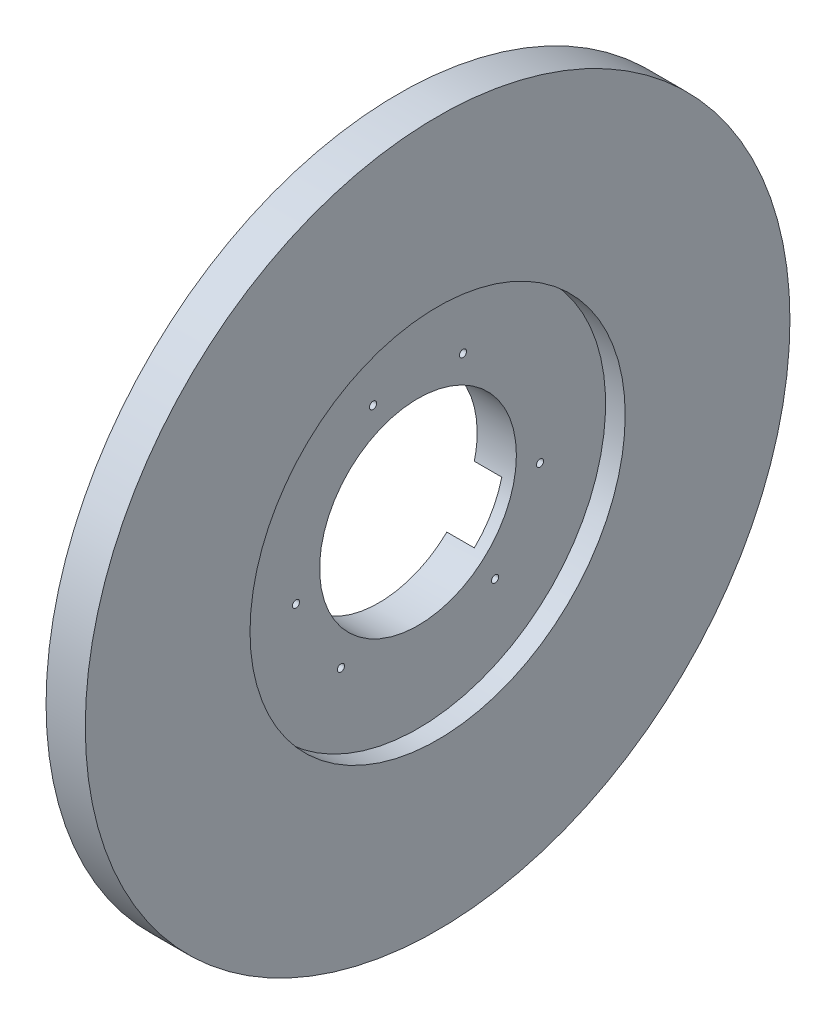
SolidWorks part; units mm, degrees
ref_plane "Front Plane" through (0, 0, 0) normal (0, 0, 1) x (1, 0, 0)
ref_plane "Top Plane" through (0, 0, 0) normal (0, 1, 0) x (1, 0, 0)
ref_plane "Right Plane" through (0, 0, 0) normal (1, 0, 0) x (0, 0, -1)
sketch "Sketch1" plane through (0, 0, 0) normal (1, 0, 0) x (0, 0, -1)
  circle A0 centre (0, 0) radius 89.825
  circle A1 centre (0, 0) radius 47.825
  dimension "D1" = 179.65
  dimension "D2" = 95.65
extrude "Boss-Extrude1" add sketch "Sketch1" along normal blind 10
sketch "Sketch3" plane through (0, 0, 0) normal (-1, 0, 0) x (0, 0, 1)
  circle A0 centre (0, 0) radius 47.825
  dimension "D1" = 95.65
extrude "tbh idk" add sketch "Sketch3" against normal blind 5
sketch "Sketch4" plane through (0, 0, 0) normal (-1, 0, 0) x (0, 0, 1)
  circle A0 centre (0, 0) radius 47.825
  dimension "D1" = 95.65
extrude "Extrusion to Fuel Man" add sketch "Sketch4" along normal blind 5
sketch "Ox Profile" plane through (-5, 0, 0) normal (-1, 0, 0) x (0, 0, 1)
  line L0 (0, 23.8051) -> (0, 34.7601) construction
  line L1 (0, -8.25) -> (0, 8.25) construction
  circle A0 centre (0, 29.2826) radius 0.8262 construction
  circle A1 centre (11.4641, 29.2826) radius 0.9146
  circle A2 centre (-11.4641, 29.2826) radius 0.9146
  point P4 (7.9201, 29.2826)
  point P6 (6.3718, 30.3708)
  point P7 (0, 0)
  point P8 (0, 0)
  point P11 (0, 29.2826)
  point P12 (0, 22.8185)
  point P13 (-2.1016, 23.1697)
  point P14 (0, 0)
  point P15 (6.1202, 27.2022)
  point P16 (0, 34.7601)
  point P19 (-6.4641, 29.2826)
  dimension "D1" = 1.6524
  dimension "D3" = 1.8292
  dimension "D2" = 29.2826
  dimension "D4" = 11.4641
extrude "Ox Downcomer" cut sketch "Ox Profile" against normal up to next
pattern_circular "Ox Orifices" count 3 over 360 about axis through (0, -0.0214, 0) along (1, 0, 0) of "Ox Downcomer"
sketch "Sketch7" plane through (-5, 0, 0) normal (-1, 0, 0) x (0, 0, 1)
  line L0 (-8.7202, 29.2826) -> (8.7202, 29.2826) construction
  line L1 (-31.0915, -4.7131) -> (-11.4641, 29.2826) construction
  line L2 (-33.4678, -3.3412) -> (-13.8404, 30.6545)
  line L3 (31.0915, -4.7131) -> (11.4641, 29.2826) construction
  line L4 (13.8404, 30.6545) -> (33.4678, -3.3412)
  line L5 (-19.6274, -24.5695) -> (19.6274, -24.5695) construction
  line L6 (-19.6274, -27.3134) -> (19.6274, -27.3134)
  circle A0 centre (-11.4641, 29.2826) radius 2.7439 construction
  circle A1 centre (11.4641, 29.2826) radius 2.7439 construction
  arc A2 (-8.7202, 29.2826) -> (8.7202, 29.2826) centre (0, 29.2826) ccw
  circle A3 centre (31.0915, -4.7131) radius 2.7439 construction
  arc A4 (29.7196, -7.0894) -> (20.9994, -22.1932) centre (25.3595, -14.6413) ccw
  circle A5 centre (19.6274, -24.5695) radius 2.7439 construction
  circle A6 centre (-19.6274, -24.5695) radius 2.7439 construction
  arc A7 (-20.9994, -22.1932) -> (-29.7196, -7.0894) centre (-25.3595, -14.6413) ccw
  circle A8 centre (-31.0915, -4.7131) radius 2.7439 construction
  arc A9 (-13.8404, 30.6545) -> (-8.7202, 29.2826) centre (-11.4641, 29.2826) cw
  arc A10 (-33.4678, -3.3412) -> (-29.7196, -7.0894) centre (-31.0915, -4.7131) ccw
  arc A11 (8.7202, 29.2826) -> (13.8404, 30.6545) centre (11.4641, 29.2826) cw
  arc A12 (29.7196, -7.0894) -> (33.4678, -3.3412) centre (31.0915, -4.7131) ccw
  arc A13 (20.9994, -22.1932) -> (19.6274, -27.3134) centre (19.6274, -24.5695) cw
  arc A14 (-20.9994, -22.1932) -> (-19.6274, -27.3134) centre (-19.6274, -24.5695) ccw
  circle A15 centre (0, 0) radius 47.825
  point P25 (0, 0)
  dimension "D2" = 2.7439
  dimension "D3" = 95.65
  dimension "D1" = 3
extrude "Fuel Blockers" cut sketch "Sketch7" against normal blind 5
sketch "Sketch8" plane through (5, 0, 0) normal (1, 0, 0) x (0, 0, -1)
  circle A0 centre (0, 0) radius 25.085
  dimension "D1" = 50.17
extrude "TI Cut Extrude" cut sketch "Sketch8" against normal through all
sketch "Sketch9" plane through (0, 0, 0) normal (-1, 0, 0) x (0, 0, 1)
  line L0 (-13.8404, 30.6545) -> (-33.4678, -3.3412) construction
  line L1 (-13.8404, 30.6545) -> (-33.4678, -3.3412)
  line L3 (33.4678, -3.3412) -> (13.8404, 30.6545)
  line L4 (-19.6274, -27.3134) -> (19.6274, -27.3134)
  line L5 (-13.8404, 30.6545) -> (-33.4678, -3.3412)
  line L6 (33.4678, -3.3412) -> (13.8404, 30.6545)
  line L7 (-19.6274, -27.3134) -> (19.6274, -27.3134)
  line L8 (-13.8404, 30.6545) -> (-33.4678, -3.3412)
  circle A0 centre (0, 0) radius 51.325
  arc A1 (13.8404, 30.6545) -> (8.7202, 29.2826) centre (11.4641, 29.2826) ccw construction
  arc A2 (-33.4678, -3.3412) -> (-29.7196, -7.0894) centre (-31.0915, -4.7131) ccw construction
  arc A3 (13.8404, 30.6545) -> (8.7202, 29.2826) centre (11.4641, 29.2826) ccw
  arc A4 (-33.4678, -3.3412) -> (-29.7196, -7.0894) centre (-31.0915, -4.7131) ccw
  arc A5 (-17.3584, -18.1092) -> (17.3584, -18.1092) centre (0, 0) ccw construction
  arc A6 (24.3622, -5.9783) -> (7.0038, 24.0874) centre (0, 0) ccw construction
  arc A7 (-7.0038, 24.0874) -> (-24.3622, -5.9783) centre (0, 0) ccw construction
  arc A8 (-17.3584, -18.1092) -> (17.3584, -18.1092) centre (0, 0) ccw
  arc A9 (24.3622, -5.9783) -> (7.0038, 24.0874) centre (0, 0) ccw
  arc A10 (-7.0038, 24.0874) -> (-24.3622, -5.9783) centre (0, 0) ccw
  arc A16 (-8.7202, 29.2826) -> (-7.0038, 24.0874) centre (0, 29.2826) ccw
  arc A17 (7.0038, 24.0874) -> (-7.0038, 24.0874) centre (0, 0) ccw
  arc A18 (7.0038, 24.0874) -> (8.7202, 29.2826) centre (0, 29.2826) ccw
  arc A19 (13.8404, 30.6545) -> (8.7202, 29.2826) centre (11.4641, 29.2826) ccw
  arc A20 (29.7196, -7.0894) -> (33.4678, -3.3412) centre (31.0915, -4.7131) ccw
  arc A21 (29.7196, -7.0894) -> (24.3622, -5.9783) centre (25.3595, -14.6413) ccw
  arc A22 (17.3584, -18.1092) -> (24.3622, -5.9783) centre (0, 0) ccw
  arc A23 (17.3584, -18.1092) -> (20.9994, -22.1932) centre (25.3595, -14.6413) ccw
  arc A24 (19.6274, -27.3134) -> (20.9994, -22.1932) centre (19.6274, -24.5695) ccw
  arc A25 (-20.9994, -22.1932) -> (-19.6274, -27.3134) centre (-19.6274, -24.5695) ccw
  arc A26 (-20.9994, -22.1932) -> (-17.3584, -18.1092) centre (-25.3595, -14.6413) ccw
  arc A27 (-24.3622, -5.9783) -> (-17.3584, -18.1092) centre (0, 0) ccw
  arc A28 (-24.3622, -5.9783) -> (-29.7196, -7.0894) centre (-25.3595, -14.6413) ccw
  arc A29 (-33.4678, -3.3412) -> (-29.7196, -7.0894) centre (-31.0915, -4.7131) ccw
  arc A30 (-8.7202, 29.2826) -> (-13.8404, 30.6545) centre (-11.4641, 29.2826) ccw
  arc A31 (-8.7202, 29.2826) -> (-7.0038, 24.0874) centre (0, 29.2826) ccw
  arc A32 (7.0038, 24.0874) -> (-7.0038, 24.0874) centre (0, 0) ccw
  arc A33 (7.0038, 24.0874) -> (8.7202, 29.2826) centre (0, 29.2826) ccw
  arc A34 (13.8404, 30.6545) -> (8.7202, 29.2826) centre (11.4641, 29.2826) ccw
  arc A35 (29.7196, -7.0894) -> (33.4678, -3.3412) centre (31.0915, -4.7131) ccw
  arc A36 (29.7196, -7.0894) -> (24.3622, -5.9783) centre (25.3595, -14.6413) ccw
  arc A37 (17.3584, -18.1092) -> (24.3622, -5.9783) centre (0, 0) ccw
  arc A38 (17.3584, -18.1092) -> (20.9994, -22.1932) centre (25.3595, -14.6413) ccw
  arc A39 (19.6274, -27.3134) -> (20.9994, -22.1932) centre (19.6274, -24.5695) ccw
  arc A40 (-20.9994, -22.1932) -> (-19.6274, -27.3134) centre (-19.6274, -24.5695) ccw
  arc A41 (-20.9994, -22.1932) -> (-17.3584, -18.1092) centre (-25.3595, -14.6413) ccw
  arc A42 (-24.3622, -5.9783) -> (-17.3584, -18.1092) centre (0, 0) ccw
  arc A43 (-24.3622, -5.9783) -> (-29.7196, -7.0894) centre (-25.3595, -14.6413) ccw
  arc A44 (-33.4678, -3.3412) -> (-29.7196, -7.0894) centre (-31.0915, -4.7131) ccw
  arc A45 (-8.7202, 29.2826) -> (-13.8404, 30.6545) centre (-11.4641, 29.2826) ccw
  arc M3 (-8.7202, 29.2826) -> (-7.0038, 24.0874) centre (0, 29.2826) ccw
  arc M4 (-7.0038, 24.0874) -> (7.0038, 24.0874) centre (0, 0) cw
  arc M5 (7.0038, 24.0874) -> (8.7202, 29.2826) centre (0, 29.2826) ccw
  arc M6 (8.7202, 29.2826) -> (13.8404, 30.6545) centre (11.4641, 29.2826) cw
  line M7 (13.8404, 30.6545) -> (33.4678, -3.3412)
  arc M8 (33.4678, -3.3412) -> (29.7196, -7.0894) centre (31.0915, -4.7131) cw
  arc M9 (29.7196, -7.0894) -> (24.3622, -5.9783) centre (25.3595, -14.6413) ccw
  arc M10 (24.3622, -5.9783) -> (17.3584, -18.1092) centre (0, 0) cw
  arc M11 (17.3584, -18.1092) -> (20.9994, -22.1932) centre (25.3595, -14.6413) ccw
  arc M12 (20.9994, -22.1932) -> (19.6274, -27.3134) centre (19.6274, -24.5695) cw
  line M13 (19.6274, -27.3134) -> (-19.6274, -27.3134)
  arc M14 (-19.6274, -27.3134) -> (-20.9994, -22.1932) centre (-19.6274, -24.5695) cw
  arc M15 (-20.9994, -22.1932) -> (-17.3584, -18.1092) centre (-25.3595, -14.6413) ccw
  arc M16 (-17.3584, -18.1092) -> (-24.3622, -5.9783) centre (0, 0) cw
  arc M17 (-24.3622, -5.9783) -> (-29.7196, -7.0894) centre (-25.3595, -14.6413) ccw
  arc M18 (-29.7196, -7.0894) -> (-33.4678, -3.3412) centre (-31.0915, -4.7131) cw
  line M19 (-33.4678, -3.3412) -> (-13.8404, 30.6545)
  arc M20 (-13.8404, 30.6545) -> (-8.7202, 29.2826) centre (-11.4641, 29.2826) cw
  dimension "D1" = 102.65
extrude "Fuel Volume" cut sketch "Sketch9" against normal blind 2 contours A0 M20 M3 M4 M5 M6 M7 M8 M9 M10 M11 M12 M13 M14 M15 M16 M17 M18 M19
equation "\"Flange_Dia\"= 179.65"
equation "\"Regen_Thickness\"= 1.5"
equation "\"Regen_To_Inner\"=2"
equation "\"Faceplate_Area\"=95.65"
equation "\"Regen_Rib_Thickness\"=1"
equation "\"Flange_Thickness\"= 10"
equation "\"Faceplate_To_Chamber_Extrusion\"=1"
equation "\"Injector_MCCN_O-Ring\"=3"
equation "\"Ox_Orifice\" = 1.829247371"
equation "\"Fuel_Orifice\"= 1.65242067"
equation "\"OxFuel_Dist_Downstream\"= 8"
equation "\"Fuel_Dist_From_Center\"=29.2826"
equation "\"OxFuel_HalfAngle\"=30"
equation "\"D1@Sketch1\"=\"Flange_Dia\""
equation "\"D2@Sketch1\"=\"Faceplate_Area\""
equation "\"D1@Boss-Extrude1\"=\"Flange_Thickness\""
equation "\"D1@Sketch3\"=\"Faceplate_Area\""
equation "\"D1@tbh idk\" = \"Flange_Thickness\" / 2"
equation "\"D1@Sketch4\"=\"Faceplate_Area\""
equation "\"D1@Extrusion to Fuel Man\" = \"Flange_Thickness\" / 2"
equation "\"D1@Ox Profile\" = \"Fuel_Orifice\""
equation "\"D2@Ox Profile\" = \"Fuel_Dist_From_Center\""
equation "\"D3@Ox Profile\" = \"Ox_Orifice\""
equation "\"D1@Flange\" = \"Flange_Thickness\""
equation "\"D1@Regen Slots Sketch\" = \"Regen_Rib_Thickness\""
equation "\"D2@Regen Slots Sketch\" = \"Regen_Thickness\""
equation "\"D3@Regen Slots Sketch\" = \"Regen_To_Inner\""
equation "\"D1@Faceplate Extrusion to Manifold Sketch\" = \"Faceplate_Area\""
equation "\"D1@Faceplate Extrusion to Chamber Sketch\" = \"Faceplate_Area\""
equation "\"D1@Faceplate Extrusion to Chamber\"=\"Faceplate_To_Chamber_Extrusion\""
equation "\"D1@O-Ring Slot Sketch\" = \"Faceplate_Area\""
equation "\"D2@O-Ring Slot Sketch\" = \"Injector_MCCN_O-Ring\""
equation "\"D1@O-Ring Slot\" =  ( \"Faceplate_To_Chamber_Extrusion\" )  +  ( \"Injector_MCCN_O-Ring\" / 2 ) "
equation "\"D1@Fuel Orifices Sketch\" = \"Ox_Orifice\""
equation "\"D2@Fuel Orifices Sketch\" = \"Fuel_Orifice\""
equation "\"D5@Fuel Orifices Sketch\" = \"Fuel_Dist_From_Center\""
equation "\"D3@Fuel Orifices Sketch\" = \"OxFuel_Dist_Downstream\""
equation "\"D4@Fuel Orifices Sketch\" = \"OxFuel_Dist_Downstream\""
equation "\"D1@Ox1 Profile\" = \"Ox_Orifice\""
equation "\"D1@Ox2 Profile\" = \"Ox_Orifice\""
equation "\"D1@Ox2 Guide Curve\" = \"OxFuel_HalfAngle\""
equation "\"D2@Ox1 Profile\" = \"OxFuel_Dist_Downstream\""
equation "\"D2@Ox2 Profile\"=\"OxFuel_Dist_Downstream\""
equation "\"D1@Ox1 Guide Curve\"=\"OxFuel_HalfAngle\""
equation "\"Thickness_FuelMan\"=5"
equation "\"D1@Faceplate Extrusion to Manifold\"=\"Thickness_FuelMan\""
equation "\"OxFuel_Dist_Upstream\"=(((\"Thickness_FuelMan\" + \"Faceplate_To_Chamber_Extrusion\")*tan(\"OxFuel_HalfAngle\")))+(\"OxFuel_Dist_Downstream\")"
equation "\"D4@Ox Profile\"=\"OxFuel_Dist_Upstream\""
equation "\"D7@Fuel Orifices Sketch\"=2*\"Fuel_Dist_From_Center\""
equation "\"D2@Sketch7\"=\"Ox_Orifice\"*1.5"
equation "\"D3@Sketch7\"=\"Faceplate_Area\""
equation "\"D1@Fuel Blockers\" = \"Thickness_FuelMan\""
equation "\"Torch_Igniter_OD\"=50.17"
equation "\"D1@Sketch8\"=\"Torch_Igniter_OD\""
equation "\"D1@Sketch9\"=\"Faceplate_Area\"+2*(\"Regen_To_Inner\"+\"Regen_Thickness\")"
equation "\"Fuel_Recess_In_OxMan\"=2"
equation "\"D1@Fuel Volume\" = \"Fuel_Recess_In_OxMan\""
